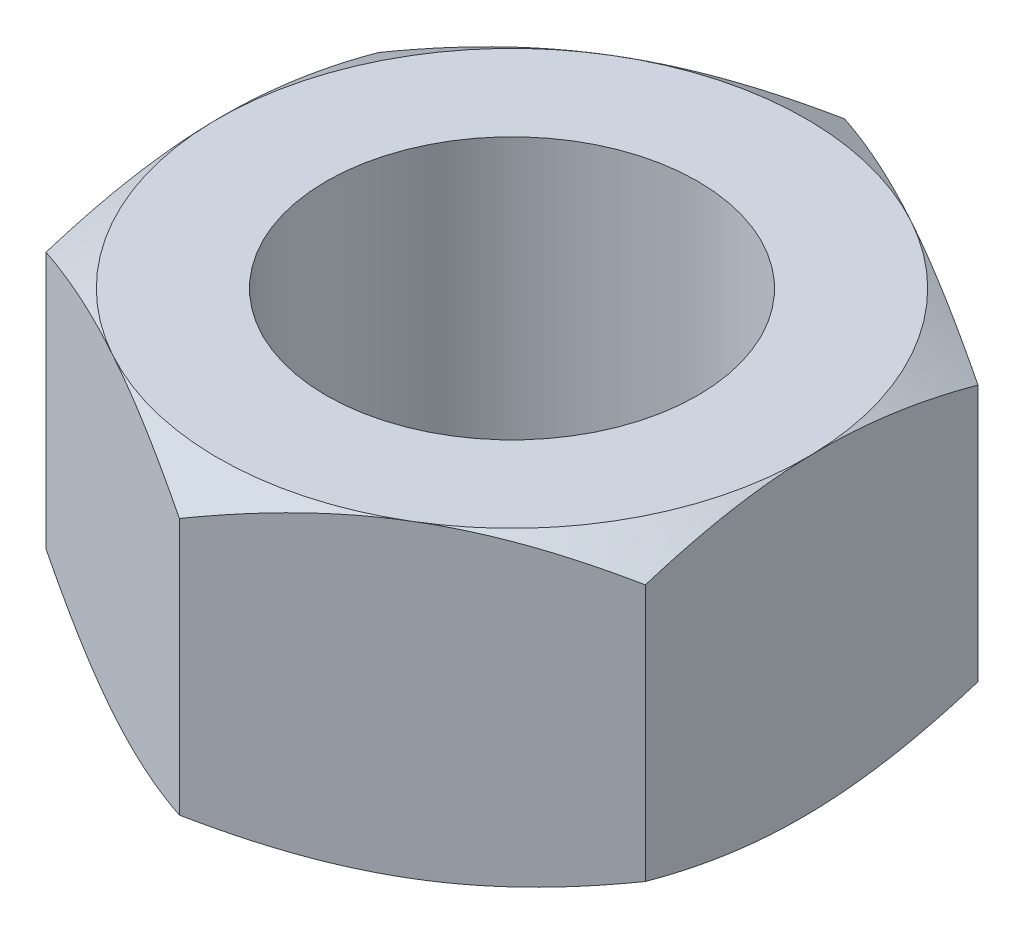
SolidWorks part; units mm, degrees
ref_plane "Front Plane" through (0, 0, 0) normal (0, 0, 1) x (1, 0, 0)
ref_plane "Top Plane" through (0, 0, 0) normal (0, 1, 0) x (1, 0, 0)
ref_plane "Right Plane" through (0, 0, 0) normal (1, 0, 0) x (0, 0, -1)
sketch "Sketch1" plane through (0, 0, 0) normal (0, 1, 0) x (1, 0, 0)
  line L0 (0, 31.4061) -> (0, -35.8399) construction
  line L1 (-35.9631, 0) -> (38.6726, 0) construction
  line L3 (9.6066, -5.2959) -> (9.3897, 5.6716)
  line L4 (9.3897, 5.6716) -> (-0.2169, 10.9675)
  line L5 (-0.2169, 10.9675) -> (-9.6066, 5.2959)
  line L6 (-9.6066, 5.2959) -> (-9.3897, -5.6716)
  line L7 (-9.3897, -5.6716) -> (0.2169, -10.9675)
  line L8 (0.2169, -10.9675) -> (9.6066, -5.2959)
  circle A0 centre (0, 0) radius 9.5 construction
  dimension "D1" = 19
extrude "Boss-Extrude1" add sketch "Sketch1" along normal blind 10
sketch "Sketch2" plane through (0, 10, 0) normal (0, 1, 0) x (1, 0, 0)
  circle A0 centre (0, 0) radius 6
extrude "Cut-Extrude1" cut sketch "Sketch2" against normal blind 10
sketch "Sketch3" plane through (0, 10, 0) normal (0, 1, 0) x (1, 0, 0)
  line L0 (9.3897, 5.6716) -> (-0.2169, 10.9675) construction
  circle A0 centre (0, 0) radius 9.5
extrude "Cut-Extrude4" cut sketch "Sketch3" against normal blind 12 draft 60 flip side to cut
sketch "Sketch4" plane through (0, 0, 0) normal (0, -1, 0) x (1, 0, 0)
  line L0 (0.2169, 10.9675) -> (9.6066, 5.2959) construction
  circle A0 centre (0, 0) radius 9.5
extrude "Cut-Extrude5" cut sketch "Sketch4" against normal blind 12 draft 60 flip side to cut
